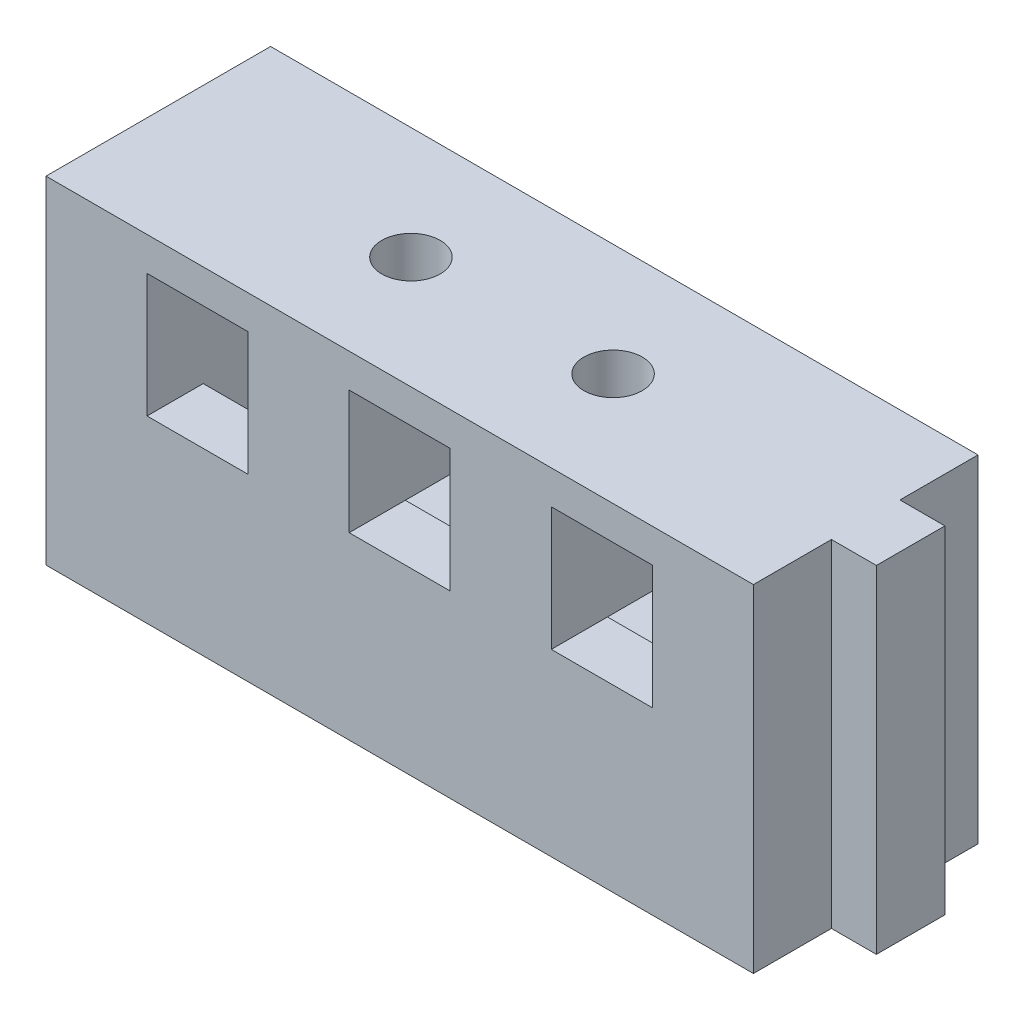
SolidWorks part; units mm, degrees
ref_plane "前视基准面" through (0, 0, 0) normal (0, 0, 1) x (1, 0, 0)
ref_plane "上视基准面" through (0, 0, 0) normal (0, 1, 0) x (1, 0, 0)
ref_plane "右视基准面" through (0, 0, 0) normal (1, 0, 0) x (0, 0, -1)
other "Configuration Table"
sketch "草图1" plane through (0, 0, 0) normal (0, 0, 1) x (1, 0, 0)
  line L0 (-13, 0) -> (50, 0)
  line L4 (50, 0) -> (50, 30)
  line L6 (-13, 30) -> (-13, 0)
  line L7 (14, 16) -> (23, 16)
  line L8 (32, 16) -> (41, 16)
  line L9 (23, 27) -> (23, 16)
  line L10 (14, 27) -> (23, 27)
  line L11 (14, 27) -> (14, 16)
  line L12 (-4, 16) -> (5, 16)
  line L13 (5, 27) -> (5, 16)
  line L14 (-4, 27) -> (5, 27)
  line L15 (32, 27) -> (41, 27)
  line L16 (32, 27) -> (32, 16)
  line L18 (41, 27) -> (41, 16)
  line L19 (-4, 27) -> (-4, 16)
  line L22 (-13, 30) -> (50, 30)
  dimension "D1" = 3
extrude "凸台-拉伸2" add sketch "草图1" along normal blind 20
sketch "草图2" plane through (0, 0, 0) normal (0, 0, -1) x (-1, 0, 0)
  line L0 (-50, 0) -> (13, 0)
  line L1 (13, 0) -> (13, 5)
  line L2 (13, 30) -> (13, 0) construction
  line L3 (13, 5) -> (-50, 5)
  line L4 (-50, 0) -> (-50, 30) construction
  line L5 (-50, 5) -> (-50, 0)
  line L7 (-50, 5) -> (4, 5)
  line L8 (-50, 5) -> (-50, 16)
  line L9 (-50, 16) -> (4, 16)
  line L10 (4, 5) -> (4, 16)
  line L11 (4, 16) -> (13, 16)
  line L12 (4, 16) -> (4, 5)
  line L13 (4, 5) -> (13, 5)
  line L14 (13, 16) -> (13, 5)
  line M14 (4, 16) -> (-5, 16)
  line M18 (-50, 30) -> (-50, 0)
  line M20 (13, 0) -> (13, 30)
  line M22 (-14, 16) -> (-23, 16)
  line M26 (-32, 16) -> (-41, 16)
extrude "切除-拉伸1" cut sketch "草图2" against normal blind 15 contours L3 L10 L9 M14 M22 M26 M18 | L11 L10 L3 M20
sketch "草图3" plane through (0, 0, 0) normal (0, 0, -1) x (-1, 0, 0)
  line L0 (13, 5) -> (-50, 5) construction
  line L1 (-50, 16) -> (-41, 16)
  line L2 (-50, 16) -> (-50, 5)
  line L3 (-50, 5) -> (-41, 5)
  line L4 (-41, 16) -> (-41, 5)
  line L5 (13, 5) -> (13, 0) construction
  line L6 (4, 16) -> (13, 16)
  line L7 (4, 16) -> (4, 5)
  line L8 (4, 5) -> (13, 5)
  line L9 (13, 16) -> (13, 5)
  line L10 (13, 5) -> (-50, 5) construction
extrude "凸台-拉伸3" add sketch "草图3" against normal blind 15
sketch "草图4" plane through (0, 0, 0) normal (0, 0, -1) x (-1, 0, 0)
  line L0 (-27.5, 16) -> (-50, 16)
  line L1 (-23, 16) -> (-32, 16) construction
  line L2 (-50, 0) -> (-50, 30) construction
  line L3 (-9.5, 16) -> (13, 16)
  line L4 (-5, 16) -> (-14, 16) construction
  line L5 (13, 30) -> (13, 0) construction
  line L6 (-9.5, 16) -> (-9.5, 0)
  line L7 (13, 0) -> (-50, 0) construction
  line L8 (-27.5, 16) -> (-27.5, 0)
sketch "草图5" plane through (0, 0, 0) normal (0, -1, 0) x (1, 0, 0)
  line L0 (9.5, 0) -> (9.5, 20)
  line L1 (9.5, 0) -> (-13, 0) construction
  line L2 (-13, 0) -> (50, 0) construction
  line L3 (-13, 20) -> (50, 20) construction
  line L4 (27.5, 0) -> (27.5, 20)
  line L5 (27.5, 0) -> (50, 0) construction
  line L6 (-13, 10) -> (9.5, 10)
  line L7 (-13, 20) -> (-13, 0) construction
  line L8 (9.5, 10) -> (27.5, 10)
  line L9 (27.5, 10) -> (50, 10)
  line L10 (50, 20) -> (50, 0) construction
  circle A0 centre (9.5, 10) radius 2.6
  circle A1 centre (27.5, 10) radius 2.6
extrude "切除-拉伸2" cut sketch "草图5" against normal blind 100 contours L8 A1 L4 | L4 A1 L8 | L9 A1 L4 | L4 A1 L9 | L0 A0 L8 | L6 A0 L0 | L0 A0 L6 | L8 A0 L0
sketch "草图6" plane through (0, 5, 0) normal (0, 1, 0) x (1, 0, 0)
  circle A0 centre (9.5, -10) radius 5
  circle A1 centre (27.5, -10) radius 5
extrude "切除-拉伸3" cut sketch "草图6" against normal blind 2
sketch "草图7" plane through (50, 0, 0) normal (1, 0, 0) x (0, 0, -1)
  line L0 (-10, 0) -> (-10, 30)
  line L1 (-20, 0) -> (0, 0) construction
  line L2 (-20, 30) -> (0, 30) construction
  line L3 (-10, 15) -> (-6.95, 15)
  line L4 (-10, 15) -> (-13.05, 15)
  line L5 (-13.05, 15) -> (-13.05, 30)
  line L6 (-6.95, 15) -> (-6.95, 0)
  line L8 (-6.95, 0) -> (-13.05, 0)
  line L9 (-6.95, 0) -> (-6.95, 30)
  line L10 (-6.95, 30) -> (-13.05, 30)
  line L11 (-13.05, 0) -> (-13.05, 30)
  line M4 (0, 30) -> (-20, 30)
  line M6 (-20, 0) -> (0, 0)
extrude "凸台-拉伸4" add sketch "草图7" along normal blind 4 contours L3 L9 L0 M4 | L5 L4 L0 M4 | L11 L0 L4 M6 | L6 L3 L0 M6
